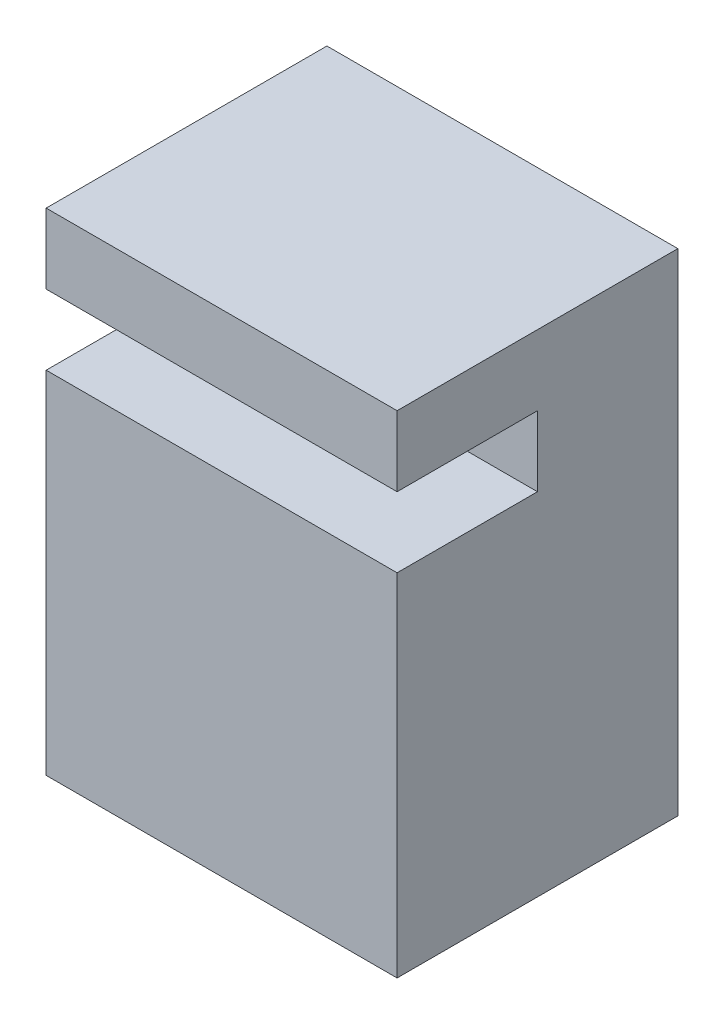
SolidWorks part; units mm, degrees
ref_plane "Front Plane" through (0, 0, 0) normal (0, 0, 1) x (1, 0, 0)
ref_plane "Top Plane" through (0, 0, 0) normal (0, 1, 0) x (1, 0, 0)
ref_plane "Right Plane" through (0, 0, 0) normal (1, 0, 0) x (0, 0, -1)
sketch "Sketch1" plane through (0, 0, 0) normal (0, 0, 1) x (1, 0, 0)
  line L1 (-25, 35) -> (25, 35)
  line L2 (-25, 35) -> (-25, -35)
  line L3 (-25, -35) -> (25, -35)
  line L4 (25, 35) -> (25, -35)
  line L5 (-25, 35) -> (25, -35) construction
  line L6 (-25, -35) -> (25, 35) construction
  point P0 (0, 0)
  dimension "D1" = 50
  dimension "D2" = 70
extrude "Boss-Extrude1" add sketch "Sketch1" against normal blind 40
sketch "Sketch2" plane through (0, 0, 0) normal (0, 0, 1) x (1, 0, 0)
  line L0 (25, -35) -> (25, 35) construction
  line L1 (-25, 25) -> (25, 25)
  line L2 (-25, 25) -> (-25, 15)
  line L3 (-25, 15) -> (25, 15)
  line L4 (25, 25) -> (25, 15)
  line L5 (-25, 25) -> (25, 15) construction
  line L6 (-25, 15) -> (25, 25) construction
  point P0 (0, 20)
  dimension "D1" = 20
  dimension "D2" = 10
  dimension "D3" = 50
extrude "Cut-Extrude1" cut sketch "Sketch2" against normal blind 20
